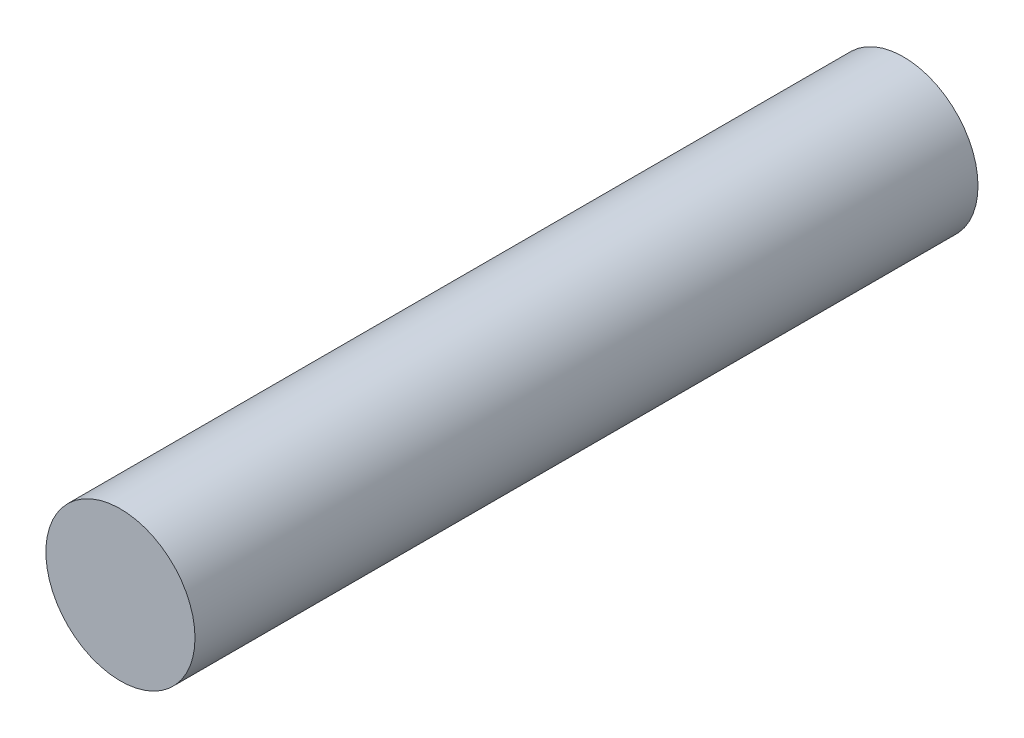
SolidWorks part; units mm, degrees
ref_plane "Спереди" through (0, 0, 0) normal (0, 0, 1) x (1, 0, 0)
ref_plane "Сверху" through (0, 0, 0) normal (0, 1, 0) x (1, 0, 0)
ref_plane "Справа" through (0, 0, 0) normal (1, 0, 0) x (0, 0, -1)
sketch "Эскиз1" plane through (0, 0, 0) normal (0, 0, 1) x (1, 0, 0)
  circle A0 centre (0, 0) radius 10
extrude "Бобышка-Вытянуть1" add sketch "Эскиз1" along normal blind 105
